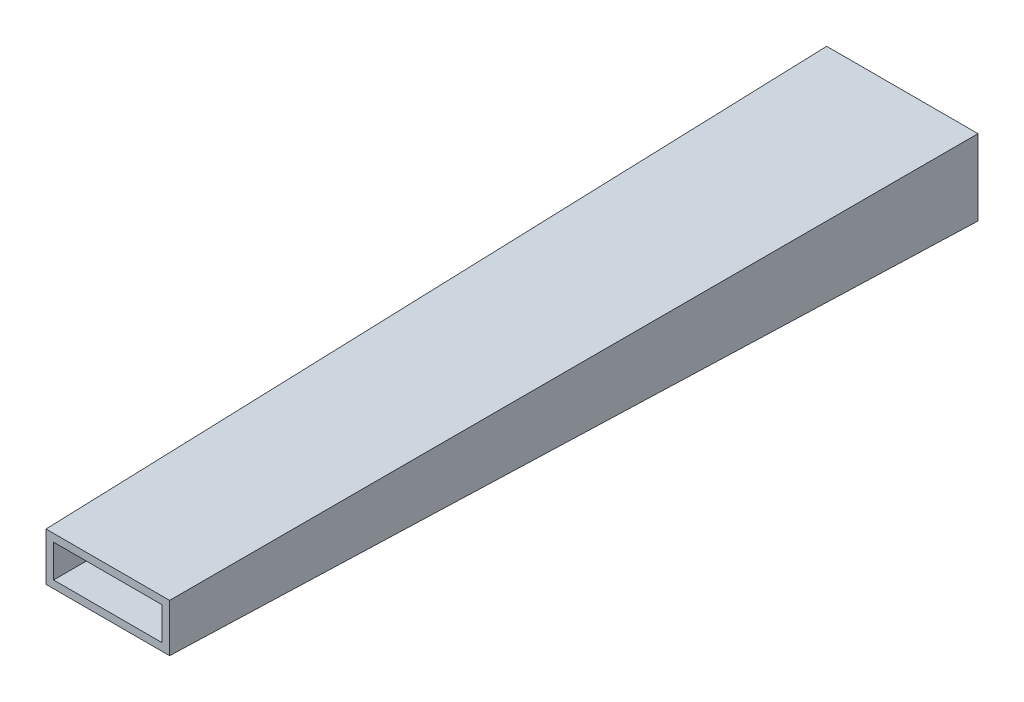
SolidWorks part; units mm, degrees
material "1060 Alloy"
ref_plane "Front Plane" through (0, 0, 0) normal (0, 0, 1) x (1, 0, 0)
ref_plane "Top Plane" through (0, 0, 0) normal (0, 1, 0) x (1, 0, 0)
ref_plane "Right Plane" through (0, 0, 0) normal (1, 0, 0) x (0, 0, -1)
sketch "Sketch2" plane through (0, 0, 0) normal (0, 0, 1) x (1, 0, 0)
  line L1 (-100, 50) -> (100, 50)
  line L2 (-100, 50) -> (-100, -50)
  line L3 (-100, -50) -> (100, -50)
  line L4 (100, 50) -> (100, -50)
  line L5 (-100, 50) -> (100, -50) construction
  line L6 (-100, -50) -> (100, 50) construction
  point P0 (0, 0)
  dimension "D1" = 100
  dimension "D2" = 200
extrude "Boss-Extrude1" add sketch "Sketch2" along normal blind 1050 draft 1
shell "Shell1" thickness 10
